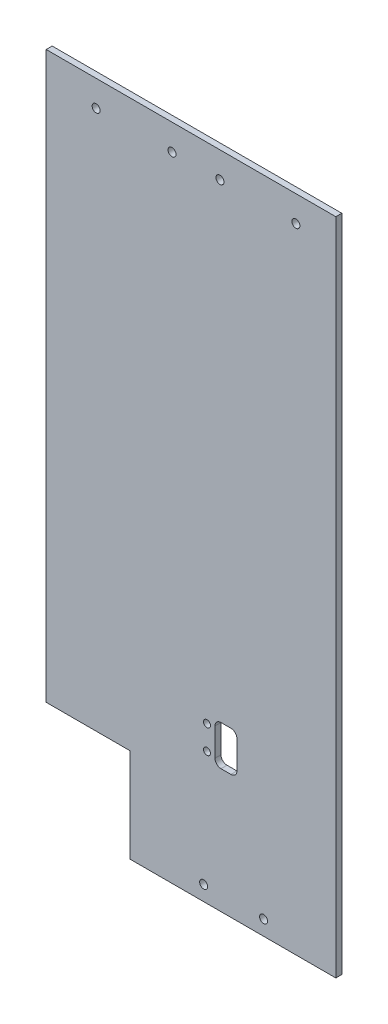
SolidWorks part; units mm, degrees
ref_plane "Plan de face" through (0, 0, 0) normal (0, 0, 1) x (1, 0, 0)
ref_plane "Plan de dessus" through (0, 0, 0) normal (0, 1, 0) x (1, 0, 0)
ref_plane "Plan de droite" through (0, 0, 0) normal (1, 0, 0) x (0, 0, -1)
sketch "Esquisse1" plane through (0, 0, 0) normal (0, 0, 1) x (1, 0, 0)
  line L1 (-37.547, 270.1613) -> (117.453, 270.1613)
  line L2 (-37.547, 270.1613) -> (-37.547, -59.8387)
  line L3 (-37.547, -59.8387) -> (117.453, -59.8387)
  line L4 (117.453, 270.1613) -> (117.453, -59.8387)
  dimension "D1" = 330
  dimension "D2" = 155
extrude "Boss.-Extru.1" add sketch "Esquisse1" along normal blind 3
sketch "Esquisse2" plane through (0, 0, 3) normal (0, 0, 1) x (1, 0, 0)
  line L0 (-27.547, -12.8387) -> (-27.547, 270.1613)
  line L1 (14.453, -12.8387) -> (-27.547, -12.8387)
  line L2 (14.453, -12.8387) -> (14.453, -59.8387)
  line L3 (14.453, -59.8387) -> (-37.547, -59.8387)
  line L4 (-37.547, -12.8387) -> (-37.547, -59.8387)
  line L5 (117.453, 270.1613) -> (-37.547, 270.1613) construction
  line L6 (-27.547, 270.1613) -> (-37.547, 270.1613)
  line L7 (-37.547, 270.1613) -> (-37.547, -12.8387)
  dimension "D1" = 52
  dimension "D2" = 47
  dimension "D3" = 10
extrude "Enlèv. mat.-Extru.1" cut sketch "Esquisse2" against normal blind 10
sketch "Esquisse3" plane through (0, 0, 3) normal (0, 0, 1) x (1, 0, 0)
  line L1 (-2.547, 257.1613) -> (97.453, 257.1613) construction
  line L2 (-27.547, -12.8387) -> (-27.547, 270.1613) construction
  circle A0 centre (51.2735, -52.3387) radius 2
  circle A1 centre (51.2735, -52.3387) radius 2 construction
  circle A2 centre (81.2735, -52.3387) radius 2
  circle A3 centre (81.2735, -52.3387) radius 2 construction
  circle A4 centre (-2.547, 257.1613) radius 2
  circle A5 centre (35.453, 257.1613) radius 2
  circle A6 centre (59.453, 257.1613) radius 2
  circle A7 centre (97.453, 257.1613) radius 2
  dimension "D5" = 4
  dimension "D1" = 25
  dimension "D2" = 63
  dimension "D3" = 87
  dimension "D4" = 125
extrude "Enlèv. mat.-Extru.2" cut sketch "Esquisse3" against normal blind 10
sketch "Esquisse4" plane through (0, 0, 3) normal (0, 0, 1) x (1, 0, 0)
  line L0 (52.953, 18.1613) -> (52.953, 6.1613) construction
  line L1 (56.953, 12.1613) -> (52.953, 12.1613) construction
  line L2 (56.953, 5.1613) -> (56.953, 19.1613)
  line L3 (59.953, 2.1613) -> (64.953, 2.1613)
  line L4 (67.953, 5.1613) -> (67.953, 19.1613)
  line L5 (59.953, 22.1613) -> (64.953, 22.1613)
  line L6 (14.453, -12.8387) -> (-27.547, -12.8387) construction
  line L7 (62.453, 22.1613) -> (62.453, 2.1613) construction
  line L8 (-27.547, -12.8387) -> (-27.547, 270.1613) construction
  circle A0 centre (52.953, 18.1613) radius 1.75
  circle A1 centre (52.953, 6.1613) radius 1.75
  arc A2 (56.953, 5.1613) -> (59.953, 2.1613) centre (59.953, 5.1613) ccw
  arc A3 (64.953, 2.1613) -> (67.953, 5.1613) centre (64.953, 5.1613) ccw
  arc A4 (67.953, 19.1613) -> (64.953, 22.1613) centre (64.953, 19.1613) ccw
  arc A5 (56.953, 19.1613) -> (59.953, 22.1613) centre (59.953, 19.1613) cw
  point P18 (56.953, 2.1613)
  point P21 (67.953, 2.1613)
  point P24 (67.953, 22.1613)
  dimension "D1" = 3.5
  dimension "D8" = 3
  dimension "D2" = 11
  dimension "D3" = 12
  dimension "D4" = 20
  dimension "D5" = 4
  dimension "D6" = 15
  dimension "D7" = 90
extrude "Enlèv. mat.-Extru.3" cut sketch "Esquisse4" against normal blind 10
